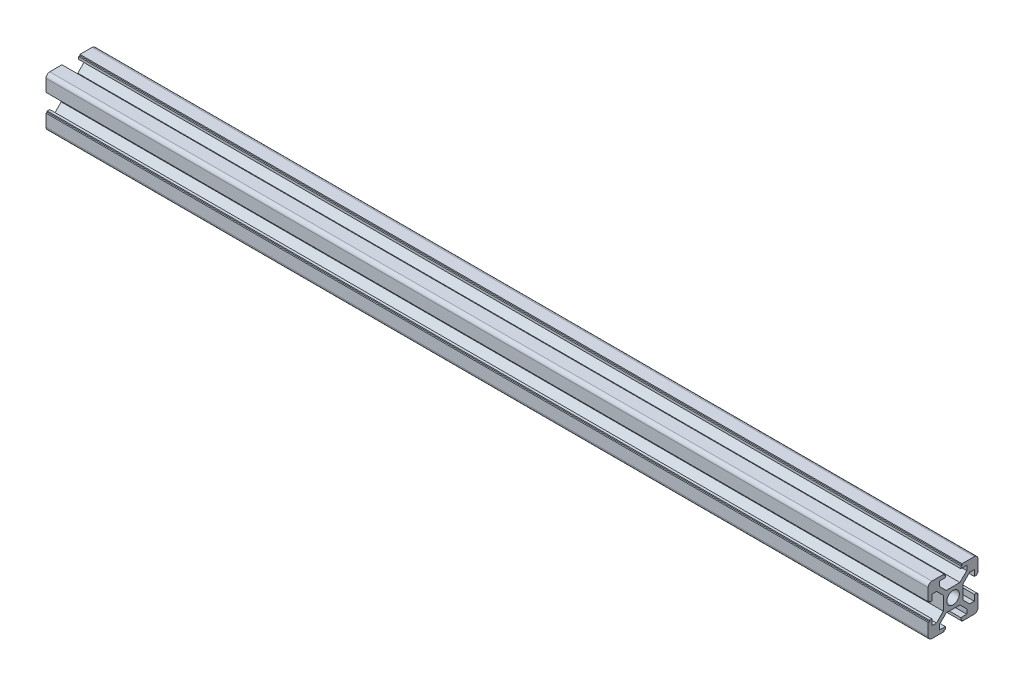
SolidWorks part; units mm, degrees
ref_plane "前视基准面" through (0, 0, 0) normal (0, 0, 1) x (1, 0, 0)
ref_plane "上视基准面" through (0, 0, 0) normal (0, 1, 0) x (1, 0, 0)
ref_plane "右视基准面" through (0, 0, 0) normal (1, 0, 0) x (0, 0, -1)
sketch "草图1" plane through (0, 0, 0) normal (0, 1, 0) x (1, 0, 0)
  line L0 (0, 0) -> (354, 0)
  dimension "D1" = 354
other "铝型材 20 X 20 X R1.5(1)"
ref_plane "基准面1" through (0, 0, 0) normal (1, 0, 0) x (0, 0, -1)
sketch "Sketch1" plane through (0, 0, 0) normal (1, 0, 0) x (0, 0, -1)
  line L0 (-3.6, 10) -> (-3.6, 9.5)
  line L1 (-3.6, 9.5) -> (-3.1, 9.5)
  line L2 (-3.1, 9.5) -> (-3.1, 8.5)
  line L3 (-3.1, 8.5) -> (-5.5, 8.5)
  line L4 (-8.5, -10) -> (-3.6, -10)
  line L5 (-10, -8.5) -> (-10, -3.6)
  line L6 (8.5, 10) -> (3.6, 10)
  line L7 (10, 8.5) -> (10, 3.6)
  line L8 (0, 14.8756) -> (0, 0) construction
  line L9 (0, 0) -> (14.1675, 0) construction
  line L10 (-5.5, 8.5) -> (-5.5, 6.65)
  line L11 (-5.5, 6.65) -> (-2.75, 3.9)
  line L12 (-2.75, 3.9) -> (2.75, 3.9)
  line L13 (5.5, 6.65) -> (2.75, 3.9)
  line L14 (5.5, 8.5) -> (5.5, 6.65)
  line L15 (3.1, 8.5) -> (5.5, 8.5)
  line L16 (3.1, 9.5) -> (3.1, 8.5)
  line L17 (3.6, 9.5) -> (3.1, 9.5)
  line L18 (3.6, 10) -> (3.6, 9.5)
  line L19 (-3.6, 10) -> (-8.5, 10)
  line L20 (10, 3.6) -> (9.5, 3.6)
  line L21 (9.5, 3.6) -> (9.5, 3.1)
  line L22 (9.5, 3.1) -> (8.5, 3.1)
  line L23 (8.5, 3.1) -> (8.5, 5.5)
  line L24 (8.5, 5.5) -> (6.65, 5.5)
  line L25 (6.65, 5.5) -> (3.9, 2.75)
  line L26 (3.9, 2.75) -> (3.9, -2.75)
  line L27 (6.65, -5.5) -> (3.9, -2.75)
  line L28 (8.5, -5.5) -> (6.65, -5.5)
  line L29 (8.5, -3.1) -> (8.5, -5.5)
  line L30 (9.5, -3.1) -> (8.5, -3.1)
  line L31 (9.5, -3.6) -> (9.5, -3.1)
  line L32 (10, -3.6) -> (9.5, -3.6)
  line L33 (3.6, -10) -> (3.6, -9.5)
  line L34 (3.6, -9.5) -> (3.1, -9.5)
  line L35 (3.1, -9.5) -> (3.1, -8.5)
  line L36 (3.1, -8.5) -> (5.5, -8.5)
  line L37 (5.5, -8.5) -> (5.5, -6.65)
  line L38 (5.5, -6.65) -> (2.75, -3.9)
  line L39 (2.75, -3.9) -> (-2.75, -3.9)
  line L40 (-5.5, -6.65) -> (-2.75, -3.9)
  line L41 (-5.5, -8.5) -> (-5.5, -6.65)
  line L42 (-3.1, -8.5) -> (-5.5, -8.5)
  line L43 (-3.1, -9.5) -> (-3.1, -8.5)
  line L44 (-3.6, -9.5) -> (-3.1, -9.5)
  line L45 (-3.6, -10) -> (-3.6, -9.5)
  line L46 (-10, -3.6) -> (-9.5, -3.6)
  line L47 (-9.5, -3.6) -> (-9.5, -3.1)
  line L48 (-9.5, -3.1) -> (-8.5, -3.1)
  line L49 (-8.5, -3.1) -> (-8.5, -5.5)
  line L50 (-8.5, -5.5) -> (-6.65, -5.5)
  line L51 (-6.65, -5.5) -> (-3.9, -2.75)
  line L52 (-3.9, -2.75) -> (-3.9, 2.75)
  line L53 (-6.65, 5.5) -> (-3.9, 2.75)
  line L54 (-8.5, 5.5) -> (-6.65, 5.5)
  line L55 (-8.5, 3.1) -> (-8.5, 5.5)
  line L56 (-9.5, 3.1) -> (-8.5, 3.1)
  line L57 (-9.5, 3.6) -> (-9.5, 3.1)
  line L58 (-10, 3.6) -> (-9.5, 3.6)
  line L59 (3.6, -10) -> (8.5, -10)
  line L60 (-10, 3.6) -> (-10, 8.5)
  line L61 (10, -3.6) -> (10, -8.5)
  circle A0 centre (0, 0) radius 2.5
  arc A1 (-10, 8.5) -> (-8.5, 10) centre (-8.5, 8.5) cw
  arc A2 (10, 8.5) -> (8.5, 10) centre (8.5, 8.5) ccw
  arc A3 (-8.5, -10) -> (-10, -8.5) centre (-8.5, -8.5) cw
  arc A4 (8.5, -10) -> (10, -8.5) centre (8.5, -8.5) ccw
  point P0 (-10, 0)
  point P1 (10, 0)
  point P2 (0, 10)
  point P3 (0, -10)
  point P4 (0, 0)
  point P5 (-10, -10)
  point P6 (10, -10)
  point P7 (10, 10)
  point P8 (-10, 10)
  point P13 (0, 0)
  point P36 (-10, 10)
  point P39 (10, 10)
  dimension "D1" = 11
  dimension "D2" = 20
  dimension "D3" = 6.2
  dimension "D4" = 7.2
  dimension "D5" = 6.1
  dimension "D6" = 5
  dimension "D7" = 1.5
  dimension "D8" = 45
  dimension "D9" = 0.5
  dimension "D10" = 1
  dimension "D11" = 5.5
